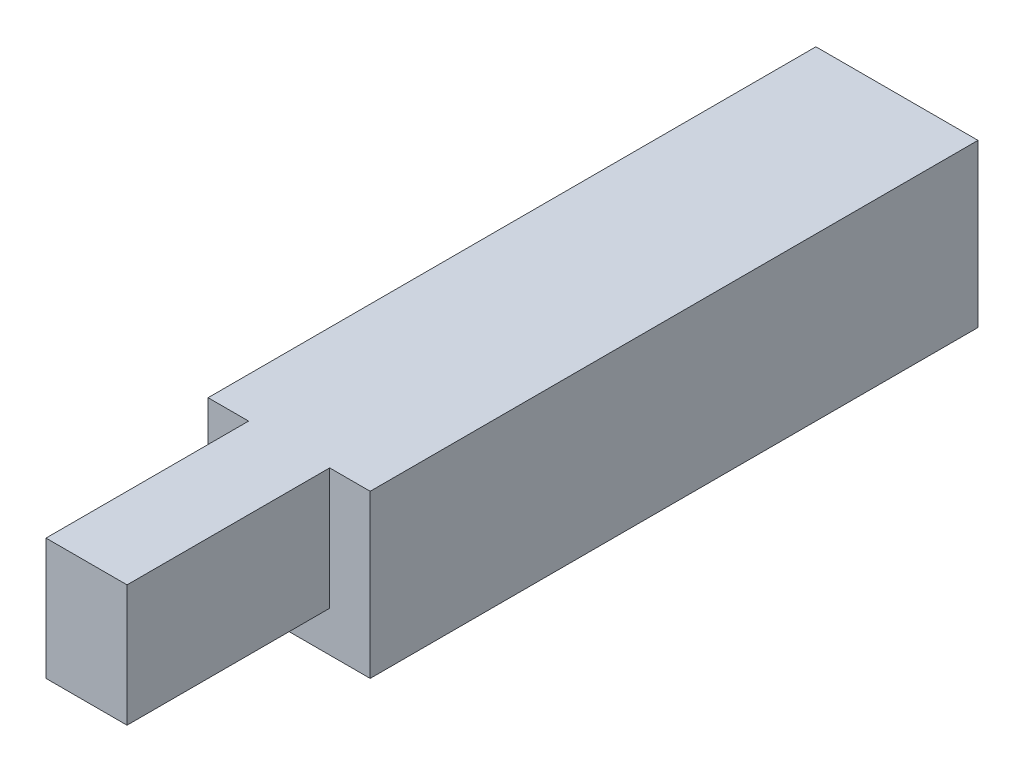
SolidWorks part; units mm, degrees
ref_plane "Front Plane" through (0, 0, 0) normal (0, 0, 1) x (1, 0, 0)
ref_plane "Top Plane" through (0, 0, 0) normal (0, 1, 0) x (1, 0, 0)
ref_plane "Right Plane" through (0, 0, 0) normal (1, 0, 0) x (0, 0, -1)
sketch "Sketch1" plane through (0, 0, 0) normal (0, 0, 1) x (1, 0, 0)
  line L1 (-5, -5) -> (5, -5)
  line L2 (-5, -5) -> (-5, 5)
  line L3 (-5, 5) -> (5, 5)
  line L4 (5, -5) -> (5, 5)
  line L5 (-5, -5) -> (5, 5) construction
  line L6 (-5, 5) -> (5, -5) construction
  point P0 (0, 0)
  dimension "D1" = 10
  dimension "D2" = 10
extrude "Boss-Extrude1" add sketch "Sketch1" along normal blind 37.5
sketch "Sketch2" plane through (0, 0, 37.5) normal (0, 0, 1) x (1, 0, 0)
  line L0 (-5, -5) -> (5, -5) construction
  line L1 (-2.5, -2.5) -> (2.5, -2.5)
  line L10 (-2.5, -2.5) -> (-2.5, 5)
  line L11 (5, 5) -> (-5, 5) construction
  line L12 (-2.5, 5) -> (2.5, 5)
  line L13 (2.5, 5) -> (2.5, -2.5)
  point P0 (0, 0)
  dimension "D1" = 2.5
sketch "Sketch3" plane through (0, 0, 37.5) normal (0, 0, 1) x (1, 0, 0)
extrude "Boss-Extrude2" add sketch "Sketch2" along normal blind 12.5
